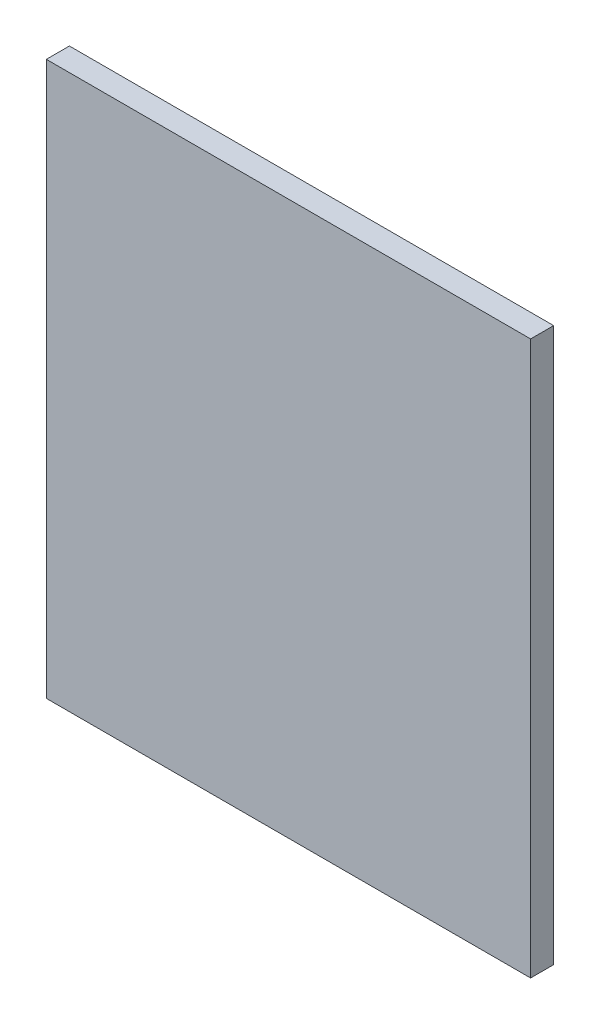
SolidWorks part; units mm, degrees
material "PMMA"
ref_plane "Front Plane" through (0, 0, 0) normal (0, 0, 1) x (1, 0, 0)
ref_plane "Top Plane" through (0, 0, 0) normal (0, 1, 0) x (1, 0, 0)
ref_plane "Right Plane" through (0, 0, 0) normal (1, 0, 0) x (0, 0, -1)
sketch "Sketch1" plane through (0, 0, 0) normal (0, 0, 1) x (1, 0, 0)
  line L1 (-52.5, 120) -> (52.5, 120)
  line L2 (-52.5, 120) -> (-52.5, 0)
  line L3 (-52.5, 0) -> (52.5, 0)
  line L4 (52.5, 120) -> (52.5, 0)
  point P4 (0, 0)
  dimension "D1" = 105
  dimension "D2" = 120
extrude "Boss-Extrude1" add sketch "Sketch1" along normal blind 5
